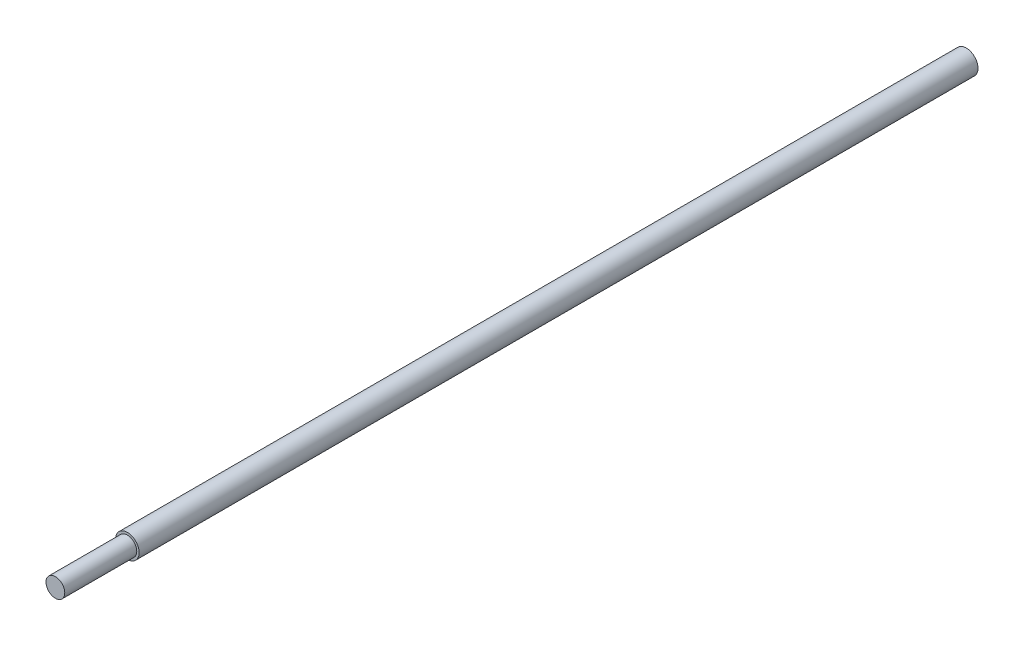
SolidWorks part; units mm, degrees
ref_plane "Front Plane" through (0, 0, 0) normal (0, 0, 1) x (1, 0, 0)
ref_plane "Top Plane" through (0, 0, 0) normal (0, 1, 0) x (1, 0, 0)
ref_plane "Right Plane" through (0, 0, 0) normal (1, 0, 0) x (0, 0, -1)
sketch "Sketch1" plane through (0, 0, 0) normal (0, 0, 1) x (1, 0, 0)
  circle A0 centre (0, 0) radius 7.5
  dimension "D1" = 15
extrude "Boss-Extrude1" add sketch "Sketch1" along normal blind 536
sketch "Sketch2" plane through (0, 0, 536) normal (0, 0, 1) x (1, 0, 0)
  circle A0 centre (0, 0) radius 6
  dimension "D1" = 12
extrude "Boss-Extrude2" add sketch "Sketch2" along normal blind 46
